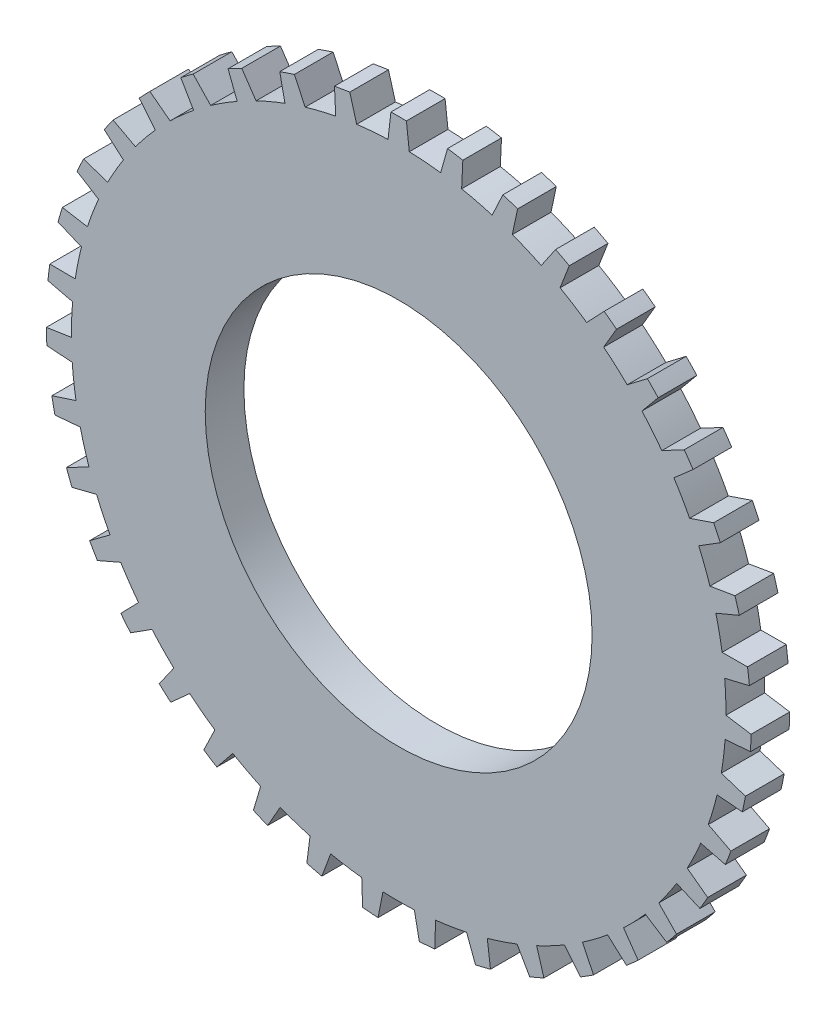
SolidWorks part; units mm, degrees
material "ABS"
ref_plane "Alzado" through (0, 0, 0) normal (0, 0, 1) x (1, 0, 0)
ref_plane "Planta" through (0, 0, 0) normal (0, 1, 0) x (1, 0, 0)
ref_plane "Vista lateral" through (0, 0, 0) normal (1, 0, 0) x (0, 0, -1)
sketch "Croquis1" plane through (0, 0, 0) normal (0, 0, 1) x (1, 0, 0)
  line L0 (0, 0) -> (0, 14.5885) construction
  line L1 (-0.4, 18.2149) -> (-0.55, 16.9103)
  line L2 (0.4, 18.2149) -> (0.55, 16.9103)
  line L3 (3.3167, 17.9148) -> (3.2555, 16.6031)
  line L4 (2.5271, 18.0432) -> (2.1697, 16.7796)
  line L5 (6.1475, 17.1508) -> (5.8767, 15.8659)
  line L6 (5.3887, 17.4041) -> (4.8333, 16.2142)
  line L7 (8.8191, 15.9426) -> (8.3456, 14.7178)
  line L8 (8.1107, 16.3144) -> (7.3716, 15.229)
  line L9 (11.2622, 14.3215) -> (10.5984, 13.1884)
  line L10 (10.6227, 14.8021) -> (9.7191, 13.8493)
  line L11 (13.4137, 12.3294) -> (12.5768, 11.3175)
  line L12 (12.8595, 12.9064) -> (11.8148, 12.1109)
  line L13 (15.2178, 10.018) -> (14.2294, 9.1535)
  line L14 (14.7633, 10.6764) -> (13.6045, 10.0588)
  line L15 (16.6277, 7.4472) -> (15.5134, 6.7524)
  line L16 (16.2848, 8.17) -> (15.0419, 7.7462)
  line L17 (17.607, 4.6835) -> (16.3957, 4.1765)
  line L18 (17.3844, 5.4519) -> (16.0897, 5.233)
  line L19 (18.1303, 1.7985) -> (16.8533, 1.4923)
  line L20 (18.0339, 2.5926) -> (16.7207, 2.5843)
  line L21 (18.184, -1.1331) -> (16.8745, -1.2305)
  line L22 (18.2162, -0.3338) -> (16.9188, -0.1314)
  line L23 (17.7668, -4.0354) -> (16.4586, -3.9214)
  line L24 (17.9268, -3.2515) -> (16.6786, -2.8436)
  line L25 (16.8894, -6.8331) -> (15.6164, -6.5107)
  line L26 (17.1731, -6.0851) -> (16.0065, -5.4822)
  line L27 (15.5746, -9.4539) -> (14.3698, -8.9315)
  line L28 (15.9746, -8.761) -> (14.9198, -7.9789)
  line L29 (13.8564, -11.8298) -> (12.751, -11.1209)
  line L30 (14.3623, -11.2101) -> (13.4467, -10.2688)
  line L31 (11.7793, -13.8993) -> (10.8019, -13.0223)
  line L32 (12.3781, -13.3688) -> (11.6253, -12.2928)
  line L33 (9.3972, -15.6088) -> (8.5731, -14.5864)
  line L34 (10.0733, -15.1813) -> (9.5028, -13.9985)
  line L35 (6.7716, -16.9141) -> (6.1223, -15.7727)
  line L36 (7.5076, -16.6005) -> (7.1343, -15.3416)
  line L37 (3.9707, -17.7813) -> (3.5129, -16.5506)
  line L38 (4.7475, -17.5899) -> (4.5809, -16.2873)
  line L39 (1.067, -18.188) -> (0.8125, -16.8998)
  line L40 (1.8644, -18.1236) -> (1.9089, -16.8112)
  line L41 (-1.8644, -18.1236) -> (-1.9089, -16.8112)
  line L42 (-1.067, -18.188) -> (-0.8125, -16.8998)
  line L43 (-4.7475, -17.5899) -> (-4.5809, -16.2873)
  line L44 (-3.9707, -17.7813) -> (-3.5129, -16.5506)
  line L45 (-7.5076, -16.6005) -> (-7.1343, -15.3416)
  line L46 (-6.7716, -16.9141) -> (-6.1223, -15.7727)
  line L47 (-10.0733, -15.1813) -> (-9.5028, -13.9985)
  line L48 (-9.3972, -15.6088) -> (-8.5731, -14.5864)
  line L49 (-12.3781, -13.3688) -> (-11.6253, -12.2928)
  line L50 (-11.7793, -13.8993) -> (-10.8019, -13.0223)
  line L51 (-14.3623, -11.2101) -> (-13.4467, -10.2688)
  line L52 (-13.8564, -11.8298) -> (-12.751, -11.1209)
  line L53 (-15.9746, -8.761) -> (-14.9198, -7.9789)
  line L54 (-15.5746, -9.4539) -> (-14.3698, -8.9315)
  line L55 (-17.1731, -6.0851) -> (-16.0065, -5.4822)
  line L56 (-16.8894, -6.8331) -> (-15.6164, -6.5107)
  line L57 (-17.9268, -3.2515) -> (-16.6786, -2.8436)
  line L58 (-17.7668, -4.0354) -> (-16.4586, -3.9214)
  line L59 (-18.2162, -0.3338) -> (-16.9188, -0.1314)
  line L60 (-18.184, -1.1331) -> (-16.8745, -1.2305)
  line L61 (-18.0339, 2.5926) -> (-16.7207, 2.5843)
  line L62 (-18.1303, 1.7985) -> (-16.8533, 1.4923)
  line L63 (-17.3844, 5.4519) -> (-16.0897, 5.233)
  line L64 (-17.607, 4.6835) -> (-16.3957, 4.1765)
  line L65 (-16.2848, 8.17) -> (-15.0419, 7.7462)
  line L66 (-16.6277, 7.4472) -> (-15.5134, 6.7524)
  line L67 (-14.7633, 10.6764) -> (-13.6045, 10.0588)
  line L68 (-15.2178, 10.018) -> (-14.2294, 9.1535)
  line L69 (-12.8595, 12.9064) -> (-11.8148, 12.1109)
  line L70 (-13.4137, 12.3294) -> (-12.5768, 11.3175)
  line L71 (-10.6227, 14.8021) -> (-9.7191, 13.8493)
  line L72 (-11.2622, 14.3215) -> (-10.5984, 13.1884)
  line L73 (-8.1107, 16.3144) -> (-7.3716, 15.229)
  line L74 (-8.8191, 15.9426) -> (-8.3456, 14.7178)
  line L75 (-5.3887, 17.4041) -> (-4.8333, 16.2142)
  line L76 (-6.1475, 17.1508) -> (-5.8767, 15.8659)
  line L77 (-8.8191, 15.9426) -> (-8.1107, 16.3144)
  line L78 (-6.1475, 17.1508) -> (-5.3887, 17.4041)
  line L79 (-2.5271, 18.0432) -> (-2.1697, 16.7796)
  line L80 (-3.3167, 17.9148) -> (-3.2555, 16.6031)
  line L81 (-3.3167, 17.9148) -> (-2.5271, 18.0432)
  arc A0 (-16.2848, 8.17) -> (-16.6277, 7.4472) centre (0, 0) ccw
  arc A1 (2.1697, 16.7796) -> (0.55, 16.9103) centre (0, 0) ccw
  arc A2 (-17.3844, 5.4519) -> (-17.607, 4.6835) centre (0, 0) ccw
  arc A3 (-18.0339, 2.5926) -> (-18.1303, 1.7985) centre (0, 0) ccw
  arc A4 (-18.2162, -0.3338) -> (-18.184, -1.1331) centre (0, 0) ccw
  arc A5 (-17.9268, -3.2515) -> (-17.7668, -4.0354) centre (0, 0) ccw
  arc A6 (-17.1731, -6.0851) -> (-16.8894, -6.8331) centre (0, 0) ccw
  arc A7 (-15.9746, -8.761) -> (-15.5746, -9.4539) centre (0, 0) ccw
  arc A8 (-14.3623, -11.2101) -> (-13.8564, -11.8298) centre (0, 0) ccw
  arc A9 (-12.3781, -13.3688) -> (-11.7793, -13.8993) centre (0, 0) ccw
  arc A10 (-10.0733, -15.1813) -> (-9.3972, -15.6088) centre (0, 0) ccw
  arc A11 (3.3167, 17.9148) -> (2.5271, 18.0432) centre (0, 0) ccw
  arc A12 (0.4, 18.2149) -> (-0.4, 18.2149) centre (0, 0) ccw
  arc A13 (-12.8595, 12.9064) -> (-13.4137, 12.3294) centre (0, 0) ccw
  arc A14 (-14.7633, 10.6764) -> (-15.2178, 10.018) centre (0, 0) ccw
  arc A15 (-10.6227, 14.8021) -> (-11.2622, 14.3215) centre (0, 0) ccw
  arc A16 (6.1475, 17.1508) -> (5.3887, 17.4041) centre (0, 0) ccw
  arc A17 (8.8191, 15.9426) -> (8.1107, 16.3144) centre (0, 0) ccw
  arc A18 (11.2622, 14.3215) -> (10.6227, 14.8021) centre (0, 0) ccw
  arc A19 (13.4137, 12.3294) -> (12.8595, 12.9064) centre (0, 0) ccw
  arc A20 (15.2178, 10.018) -> (14.7633, 10.6764) centre (0, 0) ccw
  arc A21 (16.6277, 7.4472) -> (16.2848, 8.17) centre (0, 0) ccw
  arc A22 (17.607, 4.6835) -> (17.3844, 5.4519) centre (0, 0) ccw
  arc A23 (18.1303, 1.7985) -> (18.0339, 2.5926) centre (0, 0) ccw
  arc A24 (18.184, -1.1331) -> (18.2162, -0.3338) centre (0, 0) ccw
  arc A25 (17.7668, -4.0354) -> (17.9268, -3.2515) centre (0, 0) ccw
  arc A26 (11.7793, -13.8993) -> (12.3781, -13.3688) centre (0, 0) ccw
  arc A27 (9.3972, -15.6088) -> (10.0733, -15.1813) centre (0, 0) ccw
  arc A28 (6.7716, -16.9141) -> (7.5076, -16.6005) centre (0, 0) ccw
  arc A29 (1.067, -18.188) -> (1.8644, -18.1236) centre (0, 0) ccw
  arc A30 (-1.8644, -18.1236) -> (-1.067, -18.188) centre (0, 0) ccw
  arc A31 (-4.7475, -17.5899) -> (-3.9707, -17.7813) centre (0, 0) ccw
  arc A32 (-7.5076, -16.6005) -> (-6.7716, -16.9141) centre (0, 0) ccw
  arc A33 (13.8564, -11.8298) -> (14.3623, -11.2101) centre (0, 0) ccw
  arc A34 (15.5746, -9.4539) -> (15.9746, -8.761) centre (0, 0) ccw
  arc A35 (16.8894, -6.8331) -> (17.1731, -6.0851) centre (0, 0) ccw
  arc A36 (4.8333, 16.2142) -> (3.2555, 16.6031) centre (0, 0) ccw
  arc A37 (7.3716, 15.229) -> (5.8767, 15.8659) centre (0, 0) ccw
  arc A38 (-10.5984, 13.1884) -> (-11.8148, 12.1109) centre (0, 0) ccw
  arc A39 (-0.55, 16.9103) -> (-2.1697, 16.7796) centre (0, 0) ccw
  arc A40 (-12.5768, 11.3175) -> (-13.6045, 10.0588) centre (0, 0) ccw
  arc A41 (-14.2294, 9.1535) -> (-15.0419, 7.7462) centre (0, 0) ccw
  arc A42 (-15.5134, 6.7524) -> (-16.0897, 5.233) centre (0, 0) ccw
  arc A43 (9.7191, 13.8493) -> (8.3456, 14.7178) centre (0, 0) ccw
  arc A44 (11.8148, 12.1109) -> (10.5984, 13.1884) centre (0, 0) ccw
  arc A45 (13.6045, 10.0588) -> (12.5768, 11.3175) centre (0, 0) ccw
  arc A46 (15.0419, 7.7462) -> (14.2294, 9.1535) centre (0, 0) ccw
  arc A47 (16.0897, 5.233) -> (15.5134, 6.7524) centre (0, 0) ccw
  arc A48 (16.7207, 2.5843) -> (16.3957, 4.1765) centre (0, 0) ccw
  arc A49 (16.9188, -0.1314) -> (16.8533, 1.4923) centre (0, 0) ccw
  arc A50 (16.6786, -2.8436) -> (16.8745, -1.2305) centre (0, 0) ccw
  arc A51 (16.0065, -5.4822) -> (16.4586, -3.9214) centre (0, 0) ccw
  arc A52 (14.9198, -7.9789) -> (15.6164, -6.5107) centre (0, 0) ccw
  arc A53 (13.4467, -10.2688) -> (14.3698, -8.9315) centre (0, 0) ccw
  arc A54 (11.6253, -12.2928) -> (12.751, -11.1209) centre (0, 0) ccw
  arc A55 (9.5028, -13.9985) -> (10.8019, -13.0223) centre (0, 0) ccw
  arc A56 (7.1343, -15.3416) -> (8.5731, -14.5864) centre (0, 0) ccw
  arc A57 (4.5809, -16.2873) -> (6.1223, -15.7727) centre (0, 0) ccw
  arc A58 (1.9089, -16.8112) -> (3.5129, -16.5506) centre (0, 0) ccw
  arc A59 (-0.8125, -16.8998) -> (0.8125, -16.8998) centre (0, 0) ccw
  arc A60 (-3.5129, -16.5506) -> (-1.9089, -16.8112) centre (0, 0) ccw
  arc A61 (-6.1223, -15.7727) -> (-4.5809, -16.2873) centre (0, 0) ccw
  arc A62 (-8.5731, -14.5864) -> (-7.1343, -15.3416) centre (0, 0) ccw
  arc A63 (-10.8019, -13.0223) -> (-9.5028, -13.9985) centre (0, 0) ccw
  arc A64 (-12.751, -11.1209) -> (-11.6253, -12.2928) centre (0, 0) ccw
  arc A65 (-14.3698, -8.9315) -> (-13.4467, -10.2688) centre (0, 0) ccw
  arc A66 (-15.6164, -6.5107) -> (-14.9198, -7.9789) centre (0, 0) ccw
  arc A67 (-16.4586, -3.9214) -> (-16.0065, -5.4822) centre (0, 0) ccw
  arc A68 (-16.8745, -1.2305) -> (-16.6786, -2.8436) centre (0, 0) ccw
  arc A69 (-16.8533, 1.4923) -> (-16.9188, -0.1314) centre (0, 0) ccw
  arc A70 (-16.3957, 4.1765) -> (-16.7207, 2.5843) centre (0, 0) ccw
  arc A71 (3.9707, -17.7813) -> (4.7475, -17.5899) centre (0, 0) ccw
  circle A72 centre (0, 0) radius 10
  arc A73 (-8.3456, 14.7178) -> (-9.7191, 13.8493) centre (0, 0) ccw
  arc A74 (-5.8767, 15.8659) -> (-7.3716, 15.229) centre (0, 0) ccw
  arc A75 (-3.2555, 16.6031) -> (-4.8333, 16.2142) centre (0, 0) ccw
  point P151 (0, 0)
  dimension "D1" = 1.3
  dimension "D6" = 20
  dimension "D2" = 1.1
  dimension "D3" = 0.8
  dimension "D5" = 1.625
  dimension "D4" = 39
extrude "Saliente-Extruir1" add sketch "Croquis1" along normal blind 2
